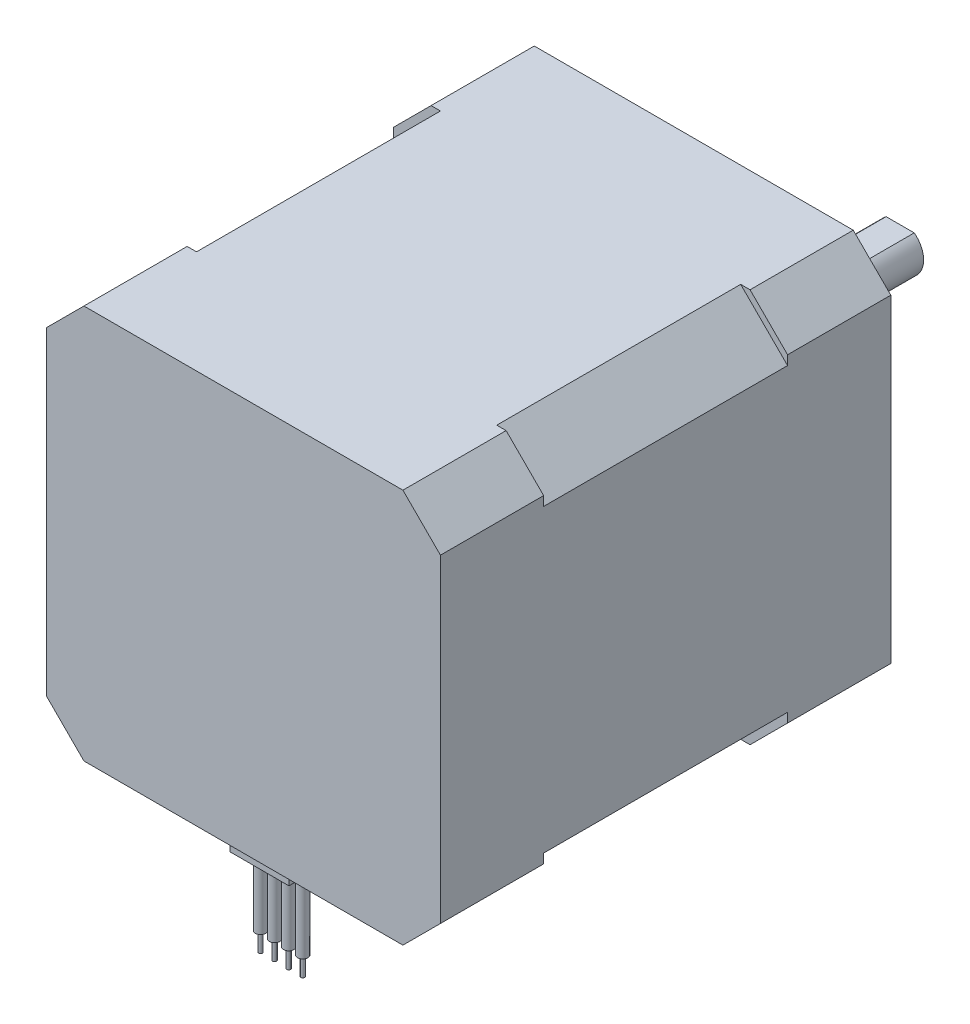
SolidWorks part; units mm, degrees
ref_plane "Plan de face" through (0, 0, 0) normal (0, 0, 1) x (1, 0, 0)
ref_plane "Plan de dessus" through (0, 0, 0) normal (0, 1, 0) x (1, 0, 0)
ref_plane "Plan de droite" through (0, 0, 0) normal (1, 0, 0) x (0, 0, -1)
sketch "Esquisse1" plane through (0, 0, 0) normal (0, 0, 1) x (1, 0, 0)
  line L0 (17, 21) -> (21, 17)
  line L1 (-17, 21) -> (17, 21)
  line L2 (-21, 17) -> (-21, -17)
  line L3 (-17, -21) -> (17, -21)
  line L4 (21, 17) -> (21, -17)
  line L5 (-21, 21) -> (21, -21) construction
  line L6 (-21, -21) -> (21, 21) construction
  line L7 (-21, 17) -> (-17, 21)
  line L8 (-21, -17) -> (-17, -21)
  line L9 (17, -21) -> (21, -17)
  point P0 (0, 0)
  dimension "D1" = 42
  dimension "D2" = 42
extrude "Boss.-Extru.1" add sketch "Esquisse1" along normal blind 11
sketch "Esquisse2" plane through (0, 0, 0) normal (0, 0, -1) x (-1, 0, 0)
  line L0 (-16, 21) -> (16, 21)
  line L1 (-17, 21) -> (17, 21) construction
  line L2 (16, 21) -> (21, 16)
  line L3 (21, 17) -> (21, -17) construction
  line L4 (21, 16) -> (21, -16)
  line L5 (21, -16) -> (16, -21)
  line L6 (17, -21) -> (-17, -21) construction
  line L7 (16, -21) -> (-16, -21)
  line L8 (-16, -21) -> (-21, -16)
  line L9 (-21, -17) -> (-21, 17) construction
  line L10 (-21, -16) -> (-21, 16)
  line L11 (-21, 16) -> (-16, 21)
  line L12 (0, 0) -> (0, 21) construction
  dimension "D1" = 5
extrude "Boss.-Extru.2" add sketch "Esquisse2" along normal blind 26
sketch "Esquisse3" plane through (0, 0, -26) normal (0, 0, -1) x (-1, 0, 0)
  line L0 (-17, 21) -> (-21, 17)
  line L1 (-21, 17) -> (-21, -17)
  line L2 (-21, -17) -> (-17, -21)
  line L3 (-17, -21) -> (17, -21)
  line L4 (17, -21) -> (21, -17)
  line L5 (21, -17) -> (21, 17)
  line L6 (21, 17) -> (17, 21)
  line L7 (17, 21) -> (-17, 21)
extrude "Boss.-Extru.3" add sketch "Esquisse3" along normal blind 11
sketch "Esquisse4" plane through (0, 0, -37) normal (0, 0, -1) x (-1, 0, 0)
  circle A0 centre (0, 0) radius 11
  dimension "D1" = 22
extrude "Boss.-Extru.4" add sketch "Esquisse4" along normal blind 2
sketch "Esquisse5" plane through (0, 0, -39) normal (0, 0, -1) x (-1, 0, 0)
  circle A0 centre (0, 0) radius 2.5
  dimension "D1" = 5
extrude "Boss.-Extru.5" add sketch "Esquisse5" along normal blind 20
sketch "Esquisse6" plane through (0, 0, -59) normal (0, 0, -1) x (-1, 0, 0)
  line L0 (0, 0) -> (0, 2) construction
  line L1 (-2.8992, 3) -> (2.8992, 3)
  line L2 (-2.8992, 3) -> (-2.8992, 2)
  line L3 (-2.8992, 2) -> (2.8992, 2)
  line L4 (2.8992, 3) -> (2.8992, 2)
  line L5 (-2.8992, 3) -> (2.8992, 2) construction
  line L6 (-2.8992, 2) -> (2.8992, 3) construction
  line L7 (0, 2) -> (0, 2.5) construction
  line L8 (0, 0) -> (0, -2.5) construction
  circle A0 centre (0, 0) radius 2.5 construction
  circle A1 centre (0, 0) radius 2.5 construction
  point P0 (0, 2.5)
  dimension "D1" = 4.5
extrude "Enlèv. mat.-Extru.1" cut sketch "Esquisse6" against normal blind 18
hole_wizard "Trou taraudé M31" positions "Esquisse7" profile "Esquisse8" tap size "M3" standard "ISO"
sketch "Esquisse7" plane through (0, 0, -37) normal (0, 0, -1) x (-1, 0, 0)
  line L0 (-15.5, 15.5) -> (15.5, 15.5) construction
  line L1 (15.5, 15.5) -> (15.5, -15.5) construction
  line L2 (15.5, -15.5) -> (-15.5, -15.5) construction
  line L3 (-15.5, -15.5) -> (-15.5, 15.5) construction
  line L4 (-15.5, 15.5) -> (15.5, -15.5) construction
  point P0 (-15.5, 15.5)
  point P2 (15.5, 15.5)
  point P4 (15.5, -15.5)
  point P6 (-15.5, -15.5)
  dimension "D1" = 31
  dimension "D2" = 31
sketch "Esquisse8" plane through (15.5, 15.5, -37) normal (1, 0, 0) x (0, 1, 0)
  line L0 (0, 0) -> (0, 7.7511)
  line L1 (0, 7.7511) -> (1.25, 7)
  line L2 (1.25, 7) -> (1.25, 0)
  line L5 (1.25, 0) -> (0, 0)
  line L10 (0, 7.7511) -> (-1.25, 7) construction
  line L11 (0, -6.35) -> (0, 107.95) construction
  dimension "Diamètre du trou pour taraudage" = 2.5
  dimension "Profondeur du trou pour taraudage" = 7
  dimension "Angle de pointe" = 118
cosmetic thread "Filetage de perçage1" parameters "D1"=4.5, "D2"=3
cosmetic thread "Filetage de perçage2" parameters "D1"=4.5, "D2"=3
cosmetic thread "Filetage de perçage3" parameters "D1"=4.5, "D2"=3
cosmetic thread "Filetage de perçage4" parameters "D1"=4.5, "D2"=3
sketch "Esquisse9" plane through (0, -21, 0) normal (0, -1, 0) x (1, 0, 0)
  line L0 (0, 0) -> (0, 4.55) construction
  line L1 (-3.15, 9.3) -> (3.15, 9.3)
  line L2 (-3.15, 9.3) -> (-3.15, 4.55)
  line L3 (-3.15, 4.55) -> (3.15, 4.55)
  line L4 (3.15, 9.3) -> (3.15, 4.55)
  line L5 (0, 4.55) -> (0, 9.3) construction
  line L6 (-17, 11) -> (17, 11) construction
  dimension "D1" = 6.3
  dimension "D2" = 4.75
  dimension "D3" = 1.7
extrude "Boss.-Extru.6" add sketch "Esquisse9" along normal blind 2.3
sketch "Esquisse10" plane through (0, -23.3, 0) normal (0, -1, 0) x (1, 0, 0)
  line L0 (-2.25, 6.925) -> (-0.75, 6.925) construction
  line L1 (-0.75, 6.925) -> (0.75, 6.925) construction
  line L2 (0.75, 6.925) -> (2.25, 6.925) construction
  line L3 (3.15, 6.925) -> (2.25, 6.925) construction
  line L4 (0, 6.925) -> (0, 0) construction
  line L5 (3.15, 4.55) -> (3.15, 9.3) construction
  circle A0 centre (-2.25, 6.925) radius 0.2025
  circle A1 centre (-0.75, 6.925) radius 0.2025
  circle A2 centre (0.75, 6.925) radius 0.2025
  circle A3 centre (2.25, 6.925) radius 0.2025
  dimension "D1" = 0.405
  dimension "D2" = 1.5
extrude "Boss.-Extru.7" add sketch "Esquisse10" along normal blind 10
sketch "Esquisse11" plane through (0, -23.3, 0) normal (0, -1, 0) x (1, 0, 0)
  circle A0 centre (-2.25, 6.925) radius 0.55
  circle A1 centre (-0.75, 6.925) radius 0.55
  circle A2 centre (0.75, 6.925) radius 0.55
  circle A3 centre (2.25, 6.925) radius 0.55
  dimension "D1" = 1.1
extrude "Boss.-Extru.8" add sketch "Esquisse11" along normal blind 8
